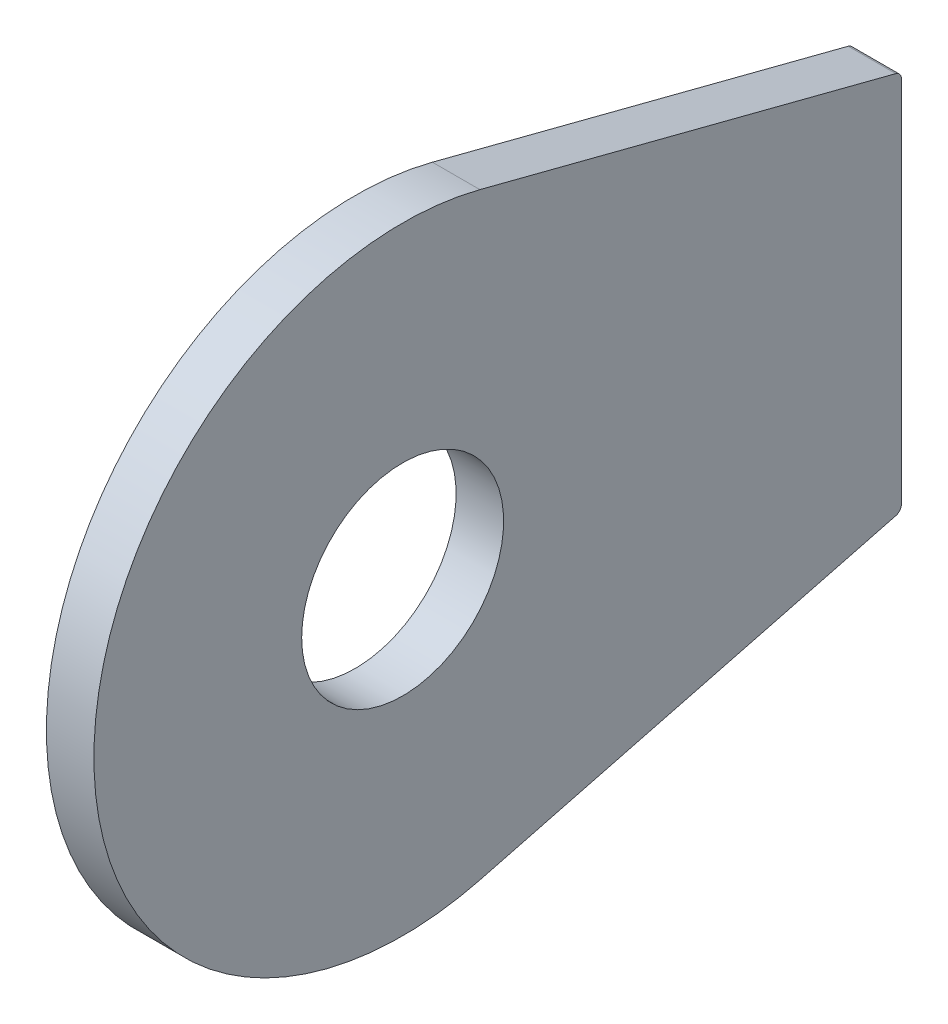
SolidWorks part; units mm, degrees
material "ASTM A36 Steel"
ref_plane "X-Y Datum" through (0, 0, 0) normal (0, 0, 1) x (1, 0, 0)
ref_plane "X-Z Datum" through (0, 0, 0) normal (0, 1, 0) x (1, 0, 0)
ref_plane "Y-Z Datum" through (0, 0, 0) normal (1, 0, 0) x (0, 0, -1)
sketch "Sketch1" plane through (0, 0, 0) normal (1, 0, 0) x (0, 0, -1)
  line L0 (33.3375, -12.7) -> (5.1638, -19.981)
  line L1 (33.3375, 12.7) -> (5.1638, 19.981)
  line L2 (33.3375, -12.7) -> (33.3375, 12.7)
  arc A0 (5.1638, 19.981) -> (5.1638, -19.981) centre (0, 0) ccw
  circle A1 centre (0, 0) radius 6.75
  dimension "D1" = 41.275
  dimension "D2" = 13.5
  dimension "D3" = 25.4
  dimension "D5" = 13.8875
extrude "Boss-Extrude1" add sketch "Sketch1" along normal mid plane 3.175 contours A1 | L0 L2 L1 A0 A1
fillet "Fillet1" radius 0.508 1 edges at (0, -12.7, -33.3375)
fillet "Fillet2" radius 0.508 1 edges at (0, 12.7, -33.3375)
hole_wizard "M12 Clearance Hole1" positions "Sketch4" profile "Sketch5" hole size "M12" standard "ANSI Metric" end condition through all
sketch "Sketch4" plane through (-1.5875, 0, 0) normal (-1, 0, 0) x (0, 0, 1)
  point P0 (0, 0)
sketch "Sketch5" plane through (-1.5875, 0, 0) normal (0, 1, 0) x (0, 0, 1)
  line L0 (0, 0) -> (0, 3.175)
  line L1 (0, 3.175) -> (6.75, 3.175)
  line L2 (6.75, 3.175) -> (6.75, 0)
  line L5 (6.75, 0) -> (0, 0)
  line L11 (0, -6.35) -> (0, 107.95) construction
  dimension "Thru Hole Dia." = 13.5
  dimension "Thru Hole Depth" = 3.175
